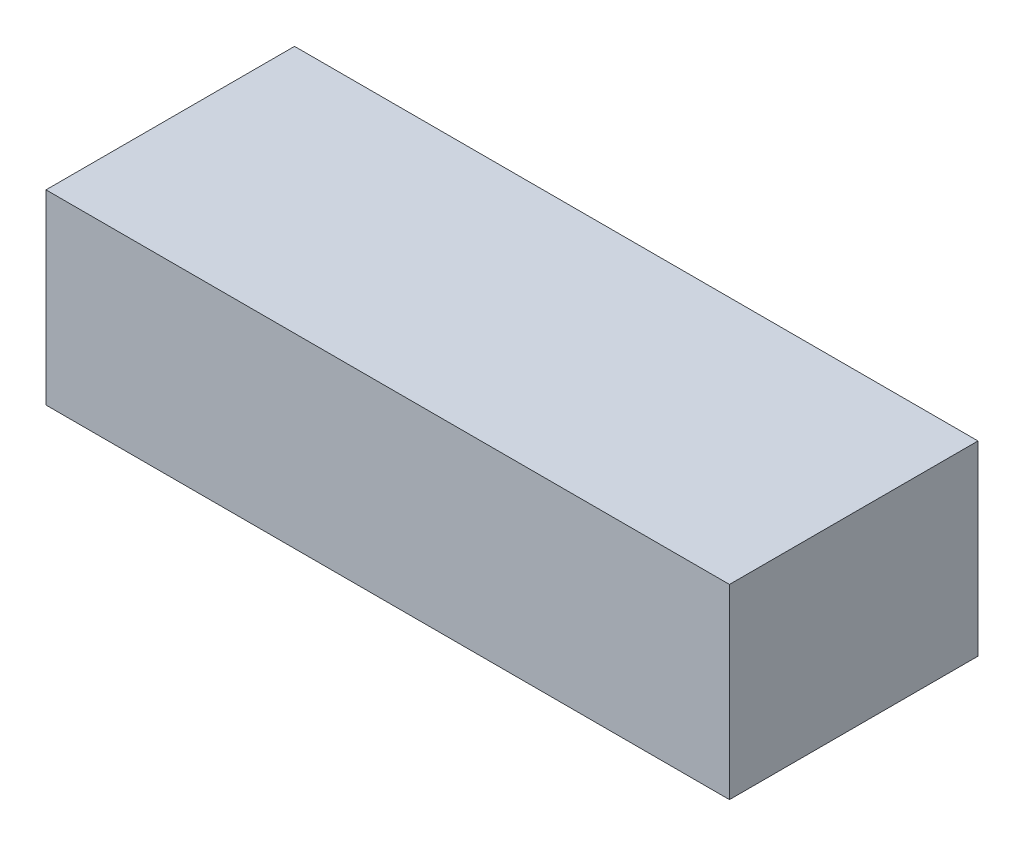
SolidWorks part; units mm, degrees
ref_plane "前视基准面" through (0, 0, 0) normal (0, 0, 1) x (1, 0, 0)
ref_plane "上视基准面" through (0, 0, 0) normal (0, 1, 0) x (1, 0, 0)
ref_plane "右视基准面" through (0, 0, 0) normal (1, 0, 0) x (0, 0, -1)
other "Configuration Table"
sketch "草图1" plane through (0, 0, 0) normal (0, 0, 1) x (1, 0, 0)
  line L1 (-22, -6) -> (22, -6)
  line L2 (-22, -6) -> (-22, 6)
  line L3 (-22, 6) -> (22, 6)
  line L4 (22, -6) -> (22, 6)
  line L5 (-22, -6) -> (22, 6) construction
  line L6 (-22, 6) -> (22, -6) construction
  point P0 (0, 0)
extrude "凸台-拉伸1" add sketch "草图1" along normal mid plane 16
